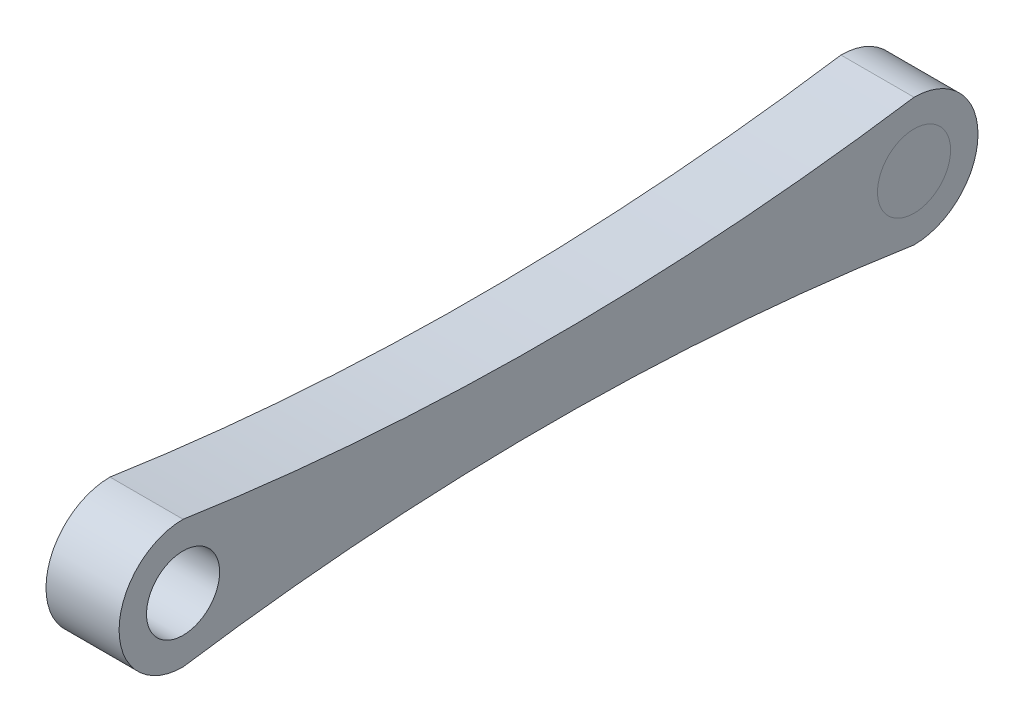
SolidWorks part; units mm, degrees
ref_plane "Front Plane" through (0, 0, 0) normal (0, 0, 1) x (1, 0, 0)
ref_plane "Top Plane" through (0, 0, 0) normal (0, 1, 0) x (1, 0, 0)
ref_plane "Right Plane" through (0, 0, 0) normal (1, 0, 0) x (0, 0, -1)
sketch "Sketch1" plane through (0, 0, 0) normal (1, 0, 0) x (0, 0, -1)
  line L2 (0, -1) -> (0, 1) construction
  arc A0 (-10, 1.75) -> (-10, -1.75) centre (-10, 0) ccw
  arc A1 (10, -1.75) -> (10, 1.75) centre (10, 0) ccw
  circle A2 centre (-10, 0) radius 1
  circle A3 centre (10, 0) radius 1
  arc A4 (-10, -1.75) -> (10, -1.75) centre (0, -68.0417) cw
  arc A5 (-10, 1.75) -> (10, 1.75) centre (0, 68.0417) ccw
  point P12 (0, 0)
  dimension "D2" = 1.75
  dimension "D3" = 2
  dimension "D1" = 20
  dimension "D4" = 2
extrude "Boss-Extrude1" add sketch "Sketch1" along normal blind 2
sketch "Sketch2" plane through (2, 0, 0) normal (1, 0, 0) x (0, 0, -1)
  circle A0 centre (10, 0) radius 1 construction
  circle A1 centre (10, 0) radius 1
extrude "Boss-Extrude2" add sketch "Sketch2" against normal up to surface (2 mm away) separate body up to face at (0, 0, 0)
